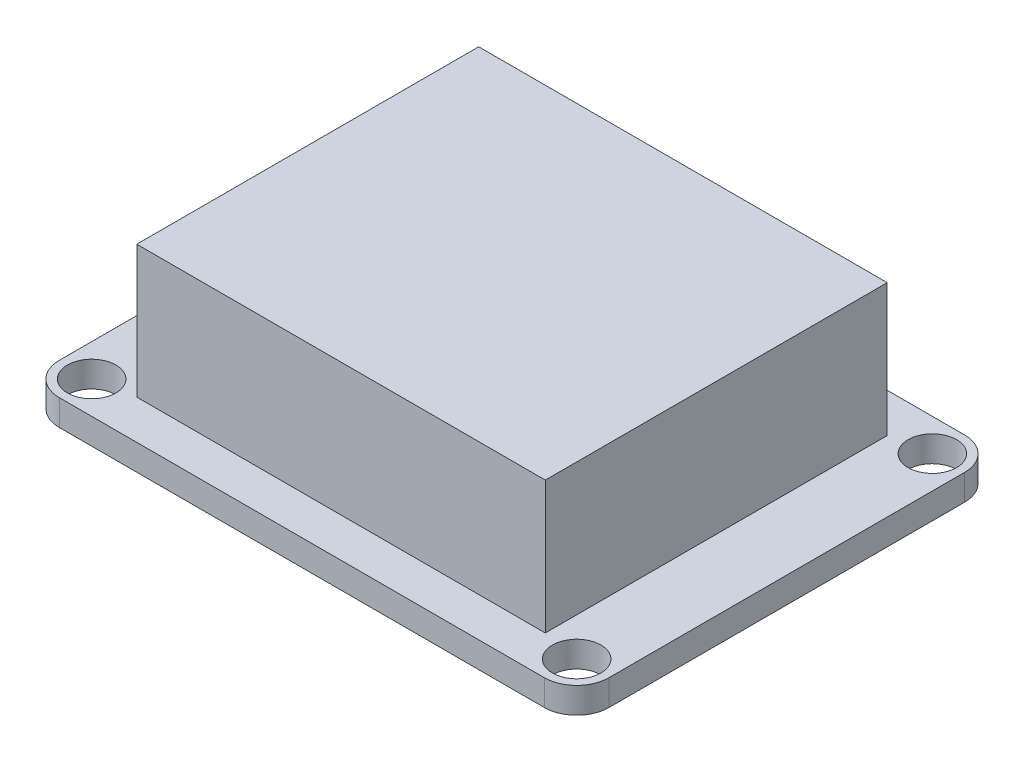
SolidWorks part; units mm, degrees
ref_plane "Front Plane" through (0, 0, 0) normal (0, 0, 1) x (1, 0, 0)
ref_plane "Top Plane" through (0, 0, 0) normal (0, 1, 0) x (1, 0, 0)
ref_plane "Right Plane" through (0, 0, 0) normal (1, 0, 0) x (0, 0, -1)
sketch "Sketch1" plane through (0, 0, 0) normal (0, 1, 0) x (1, 0, 0)
  line L1 (17, 13) -> (-17, 13)
  line L2 (17, 13) -> (17, -13)
  line L3 (17, -13) -> (-17, -13)
  line L4 (-17, 13) -> (-17, -13)
  line L5 (17, 13) -> (-17, -13) construction
  line L6 (17, -13) -> (-17, 13) construction
  point P0 (0, 0)
  dimension "D1" = 34
  dimension "D2" = 26
extrude "Boss-Extrude1" add sketch "Sketch1" along normal blind 1.6
fillet "Fillet1" radius 2 4 edges at (17, 0.8, -13) (17, 0.8, 13) (-17, 0.8, 13) (-17, 0.8, -13)
sketch "Sketch4" plane through (0, 1.6, 0) normal (0, 1, 0) x (1, 0, 0)
  line L1 (-12.635, 10.575) -> (12.635, 10.575)
  line L2 (-12.635, 10.575) -> (-12.635, -10.575)
  line L3 (-12.635, -10.575) -> (12.635, -10.575)
  line L4 (12.635, 10.575) -> (12.635, -10.575)
  line L5 (0, 0) -> (0, 10.575) construction
  line L6 (0, 0) -> (-12.635, 0) construction
  dimension "D1" = 21.15
  dimension "D2" = 25.27
extrude "Boss-Extrude3" add sketch "Sketch4" along normal blind 8.19 contours L2 L1 L4 L3
sketch "Sketch5" plane through (0, 1.6, 0) normal (0, 1, 0) x (1, 0, 0)
  line L0 (17, 0) -> (0, 0) construction
  line L1 (17, -11) -> (17, 11) construction
  line L2 (0, 0) -> (0, 12.8601) construction
  line L3 (-15, -13) -> (15, -13) construction
  circle A0 centre (15, 11) radius 1.5
  circle A1 centre (15, -11) radius 1.5
  circle A2 centre (-15, -11) radius 1.5
  circle A3 centre (-15, 11) radius 1.5
  point P14 (0, 0)
  point P15 (0, 0)
  point P16 (0, 0)
  point P17 (0, 0)
  dimension "D1" = 3
  dimension "D2" = 2
  dimension "D3" = 2
extrude "Cut-Extrude1" cut sketch "Sketch5" against normal through all both and the other way through all
